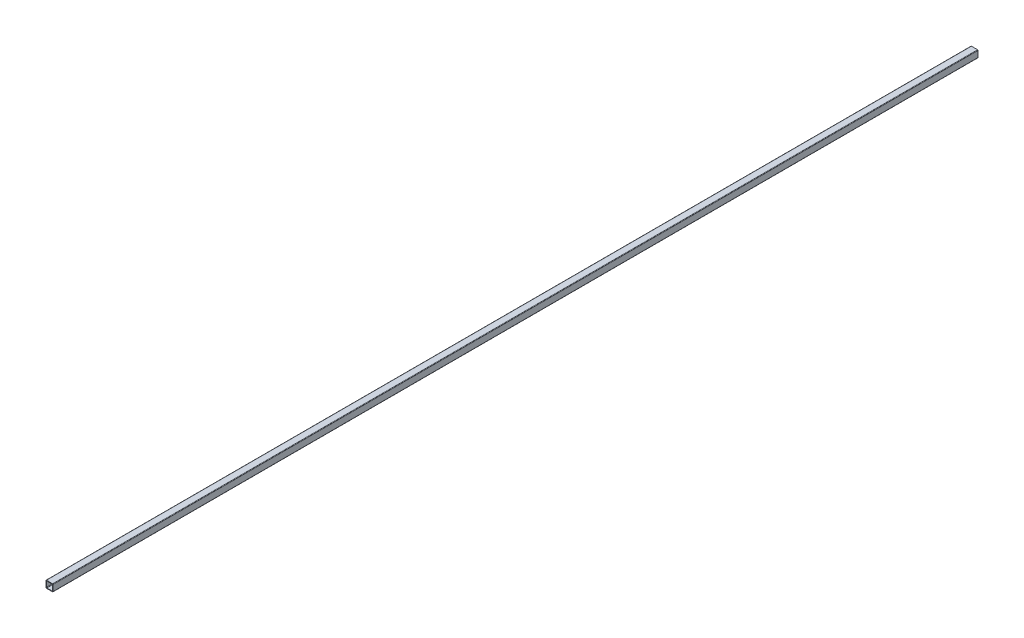
SolidWorks part; units mm, degrees
material "ASTM A500 Grade B Steel"
ref_plane "Front Plane" through (0, 0, 0) normal (0, 0, 1) x (1, 0, 0)
ref_plane "Top Plane" through (0, 0, 0) normal (0, 1, 0) x (1, 0, 0)
ref_plane "Right Plane" through (0, 0, 0) normal (1, 0, 0) x (0, 0, -1)
sketch "Sketch1" plane through (0, 0, 0) normal (0, 0, 1) x (1, 0, 0)
  line L0 (5.3086, -2.7686) -> (32.7914, -2.7686)
  line L1 (2.54, 0) -> (35.56, 0)
  line L2 (0, -2.54) -> (0, -35.56)
  line L3 (2.54, -38.1) -> (35.56, -38.1)
  line L4 (38.1, -2.54) -> (38.1, -35.56)
  line L5 (35.3314, -5.3086) -> (35.3314, -32.7914)
  line L6 (5.3086, -35.3314) -> (32.7914, -35.3314)
  line L7 (2.7686, -5.3086) -> (2.7686, -32.7914)
  line L8 (0, 0) -> (0, -38.1) construction
  line L9 (0, -38.1) -> (38.1, -38.1) construction
  line L10 (38.1, 0) -> (38.1, -38.1) construction
  line L11 (2.7686, -2.7686) -> (2.7686, -35.3314) construction
  line L12 (2.7686, -35.3314) -> (35.3314, -35.3314) construction
  line L13 (35.3314, -2.7686) -> (35.3314, -35.3314) construction
  line L14 (2.7686, -2.7686) -> (35.3314, -2.7686) construction
  line L15 (0, 0) -> (38.1, 0) construction
  arc A0 (0, -35.56) -> (2.54, -38.1) centre (2.54, -35.56) ccw
  arc A1 (38.1, -35.56) -> (35.56, -38.1) centre (35.56, -35.56) cw
  arc A2 (2.7686, -32.7914) -> (5.3086, -35.3314) centre (5.3086, -32.7914) ccw
  arc A3 (32.7914, -35.3314) -> (35.3314, -32.7914) centre (32.7914, -32.7914) ccw
  arc A4 (35.3314, -5.3086) -> (32.7914, -2.7686) centre (32.7914, -5.3086) ccw
  arc A5 (38.1, -2.54) -> (35.56, 0) centre (35.56, -2.54) ccw
  arc A6 (0, -2.54) -> (2.54, 0) centre (2.54, -2.54) cw
  arc A7 (5.3086, -2.7686) -> (2.7686, -5.3086) centre (5.3086, -5.3086) ccw
  point P12 (0, -38.1)
  dimension "D4" = 2.54
  dimension "D3" = 2.7686
extrude "Boss-Extrude1" add sketch "Sketch1" along normal blind 5020
